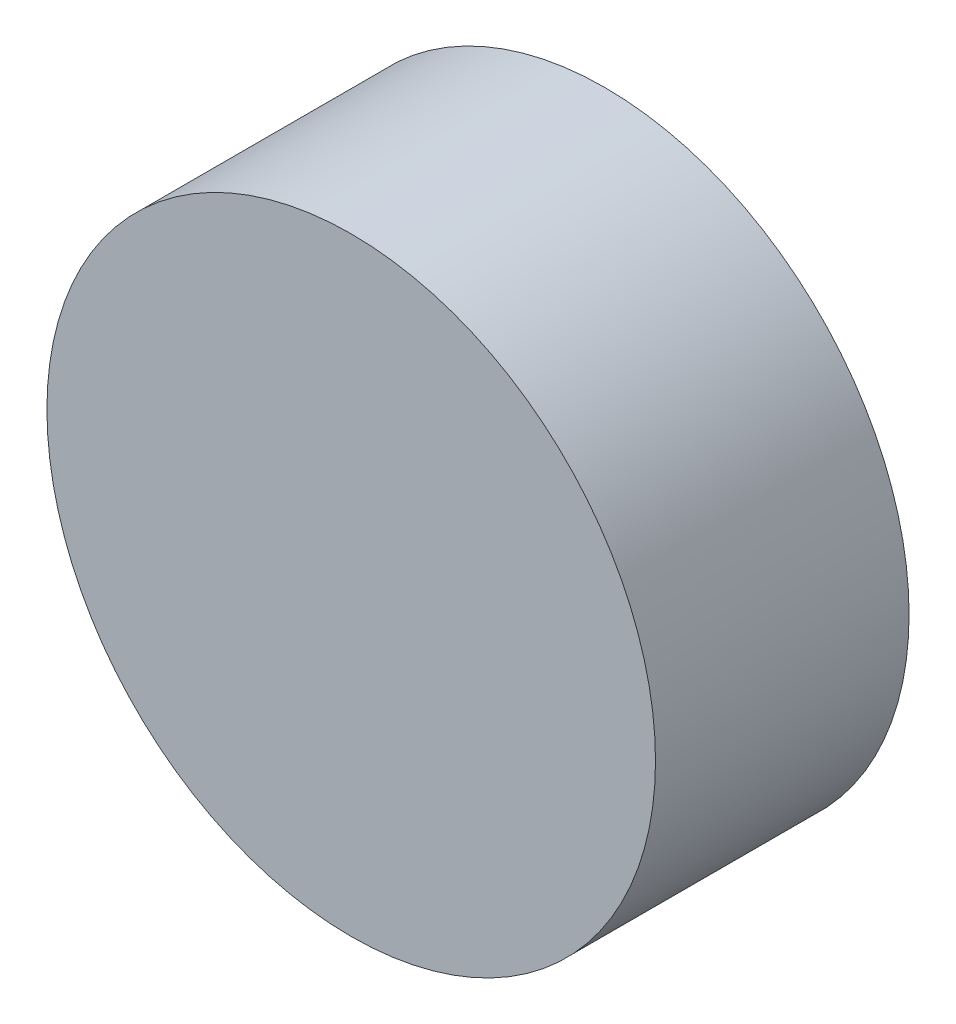
SolidWorks part; units mm, degrees
ref_plane "前基準面" through (0, 0, 0) normal (0, 0, 1) x (1, 0, 0)
ref_plane "上基準面" through (0, 0, 0) normal (0, 1, 0) x (1, 0, 0)
ref_plane "右基準面" through (0, 0, 0) normal (1, 0, 0) x (0, 0, -1)
sketch "草圖1" plane through (0, 0, 0) normal (0, 0, 1) x (1, 0, 0)
  circle A0 centre (-267.4995, 75.8854) radius 3.6
extrude "填料-伸長1" add sketch "草圖1" against normal blind 3
